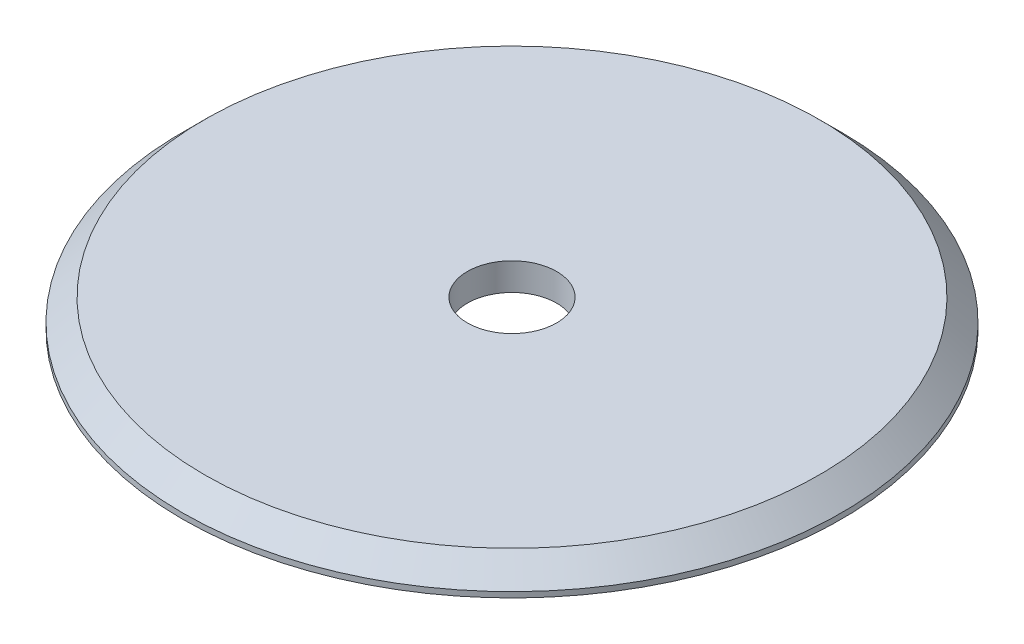
SolidWorks part; units mm, degrees
ref_plane "Ebene vorne" through (0, 0, 0) normal (0, 0, 1) x (1, 0, 0)
ref_plane "Ebene oben" through (0, 0, 0) normal (0, 1, 0) x (1, 0, 0)
ref_plane "Ebene rechts" through (0, 0, 0) normal (1, 0, 0) x (0, 0, -1)
sketch "Skizze1" plane through (0, 0, 0) normal (0, 1, 0) x (1, 0, 0)
  circle A0 centre (0, 0) radius 24
  circle A1 centre (0, 0) radius 3.25
  dimension "D1" = 48
  dimension "D2" = 6.5
extrude "Aufsatz-Linear austragen1" add sketch "Skizze1" along normal blind 2
chamfer "Fase1" distance 1.6 angle 45 1 edges at (0, 2, 24)
sketch "Skizze2" plane through (0, 0, 0) normal (0, -1, 0) x (1, 0, 0)
  circle A0 centre (0, 0) radius 14
  circle A1 centre (0, 0) radius 12
  dimension "D1" = 28
  dimension "D2" = 24
extrude "Aufsatz-Linear austragen2" add sketch "Skizze2" along normal blind 0.6
